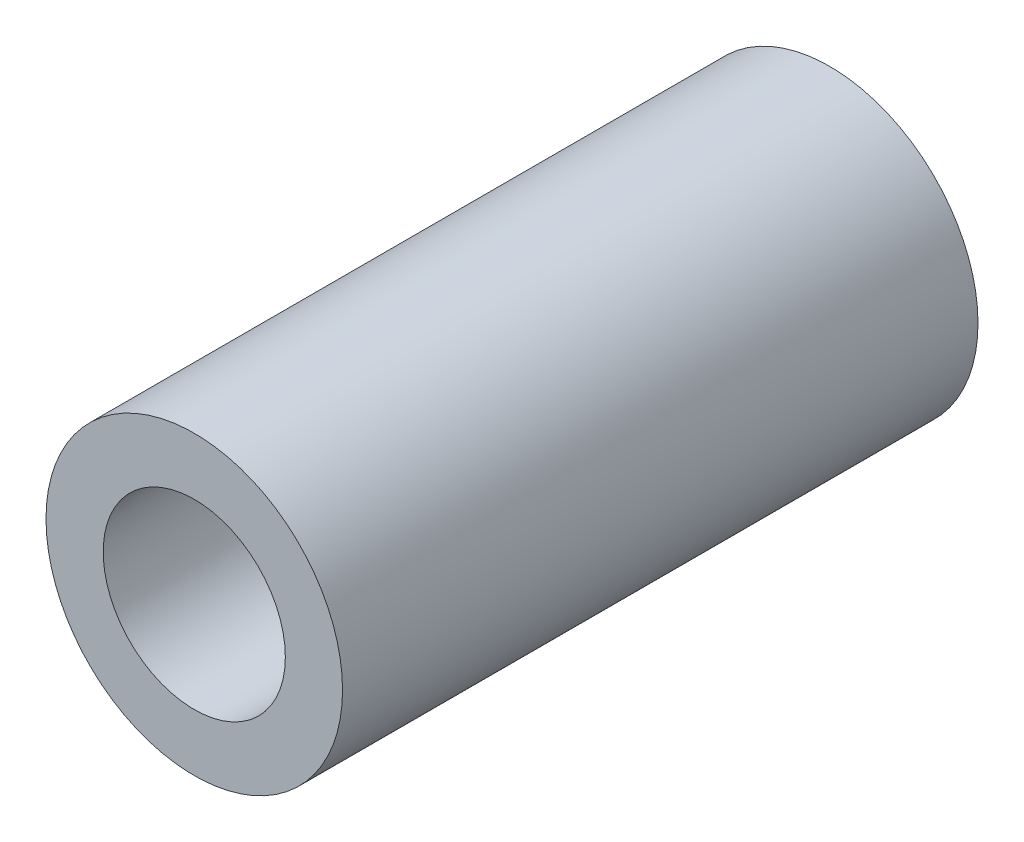
SolidWorks part; units mm, degrees
material "ABS"
ref_plane "Front" through (0, 0, 0) normal (0, 0, 1) x (1, 0, 0)
ref_plane "Top" through (0, 0, 0) normal (0, 1, 0) x (1, 0, 0)
ref_plane "Right" through (0, 0, 0) normal (1, 0, 0) x (0, 0, -1)
sketch "Эскиз1" plane through (0, 0, 0) normal (0, 0, 1) x (1, 0, 0)
  circle A0 centre (0, 0) radius 2.15
  circle A1 centre (0, 0) radius 3.5
  dimension "D1" = 4.3
  dimension "D2" = 7
extrude "Бобышка-Вытянуть1" add sketch "Эскиз1" along normal blind 15
